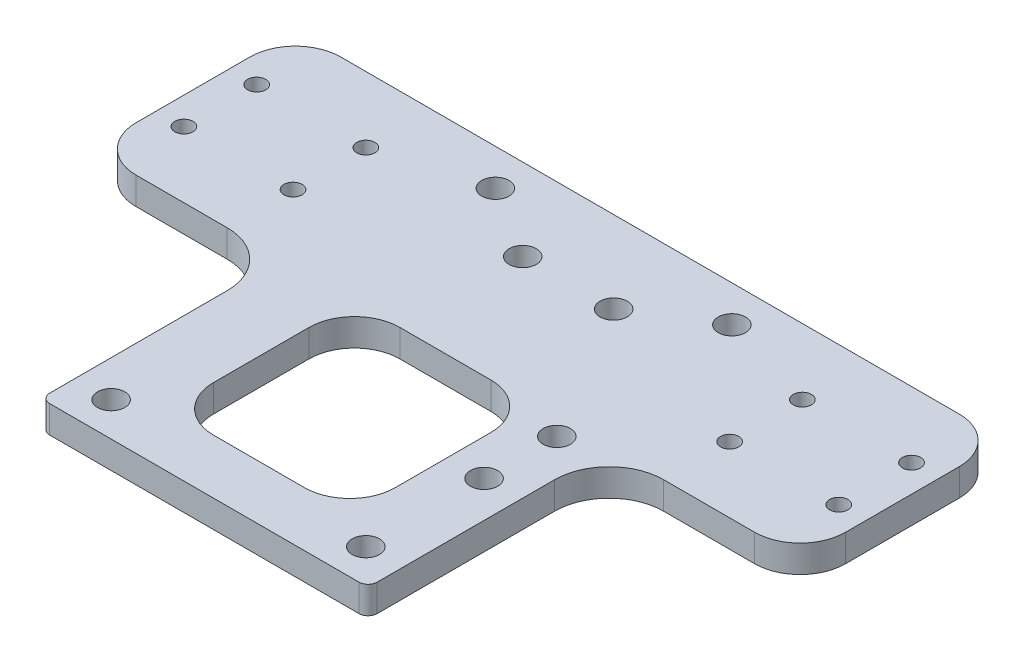
SolidWorks part; units mm, degrees
material "Thornel Mat VMA"
ref_plane "前视基准面" through (0, 0, 0) normal (0, 0, 1) x (1, 0, 0)
ref_plane "上视基准面" through (0, 0, 0) normal (0, 1, 0) x (1, 0, 0)
ref_plane "右视基准面" through (0, 0, 0) normal (1, 0, 0) x (0, 0, -1)
other "Configuration Table"
sketch "草图1" plane through (0, 0, 0) normal (0, 1, 0) x (1, 0, 0)
  line L0 (0, 0) -> (0, 37.5652) construction
  line L1 (-39, -11.25) -> (39, -11.25)
  line L2 (-39, -11.25) -> (-39, 11.25)
  line L3 (-39, 11.25) -> (39, 11.25)
  line L4 (39, -11.25) -> (39, 11.25)
  line L5 (-39, -11.25) -> (39, 11.25) construction
  line L6 (-39, 11.25) -> (39, -11.25) construction
  line L7 (0, 0) -> (52.1691, 0) construction
  line L8 (30, 0) -> (30, 35.0489) construction
  circle A0 centre (36, 4) radius 1
  circle A1 centre (24, 4) radius 1
  circle A2 centre (36, -4) radius 1
  circle A3 centre (24, -4) radius 1
  circle A4 centre (-24, -4) radius 1
  circle A5 centre (-36, -4) radius 1
  circle A6 centre (-24, 4) radius 1
  circle A7 centre (-36, 4) radius 1
  point P0 (0, 0)
  dimension "D3" = 2
  dimension "D4" = 12
  dimension "D5" = 8
  dimension "D1" = 78
  dimension "D2" = 22.5
  dimension "D6" = 30
extrude "凸台-拉伸1" add sketch "草图1" along normal blind 3
fillet "圆角1" radius 5 4 edges at (-39, 1.5, -11.25) (-39, 1.5, 11.25) (39, 1.5, -11.25) (39, 1.5, 11.25)
sketch "草图2" plane through (0, 3, 0) normal (0, 1, 0) x (1, 0, 0)
  line L0 (0, 0) -> (0, 76.4951) construction
  line L1 (0, 0) -> (49.7952, 0) construction
  line L2 (-10, -11.25) -> (-18, -11.25)
  line L12 (-10, -37.75) -> (10, -37.75)
  line L73 (-34, -11.25) -> (34, -11.25) construction
  line L74 (18, -11.25) -> (18, -37.75)
  line L79 (10, -37.75) -> (18, -37.75)
  line L80 (10, -37.75) -> (10, -11.25)
  line L81 (10, -11.25) -> (18, -11.25)
  line L82 (-10, -37.75) -> (-10, -11.25)
  line L83 (-10, -37.75) -> (-18, -37.75)
  line L84 (-18, -11.25) -> (-18, -37.75)
  line L85 (-10, -31.75) -> (10, -31.75)
  circle A0 centre (14, -8) radius 1.5
  circle A1 centre (14, -21) radius 1.5
  circle A2 centre (-14, -21) radius 1.5
  circle A3 centre (-14, -8) radius 1.5
  point P85 (0, -11.25)
  line M8 (-34, -11.25) -> (34, -11.25)
  dimension "D20" = 3
  dimension "D21" = 3
  dimension "D22" = 13
  dimension "D23" = 8
  dimension "D25" = 14
  dimension "D3" = 6
  dimension "D18" = 26.5
  dimension "D19" = 10
  dimension "D24" = 14
  dimension "D26" = 8
extrude "凸台-拉伸2" add sketch "草图2" against normal blind 3 contours L84 L83 L82 A2 M8 | A2 | L80 L79 L74 A1 M8 | L85 L82 L12 L80
sketch "草图4" plane through (0, 3, 0) normal (0, 1, 0) x (1, 0, 0)
  line L0 (0, 0) -> (0, 68.3495) construction
  line L2 (34, 11.25) -> (-34, 11.25) construction
  circle A2 centre (13, 7.25) radius 1.5
  circle A3 centre (-13, 7.25) radius 1.5
  circle A5 centre (5, 2.25) radius 1.5
  circle A6 centre (-5, 2.25) radius 1.5
  dimension "D1" = 3
  dimension "D2" = 10
  dimension "D4" = 3
  dimension "D5" = 13
  dimension "D6" = 4
  dimension "D3" = 5
extrude "切除-拉伸1" cut sketch "草图4" against normal blind 29.5
sketch "草图6" plane through (0, 3, 0) normal (0, 1, 0) x (1, 0, 0)
  line L0 (0, 0) -> (0, -39.0261) construction
  line L1 (0, 0) -> (42.2045, 0) construction
  circle A0 centre (14, -13) radius 1.5
  circle A2 centre (-14, -13) radius 1.5
  dimension "D1" = 3
  dimension "D3" = 13
  dimension "D2" = 14
extrude "切除-拉伸3" cut sketch "草图6" against normal blind 39 contours A0
fillet "圆角7" radius 6 2 edges at (18, 1.5, 11.25) (-18, 1.5, 11.25)
sketch "草图7" plane through (0, 3, 0) normal (0, 1, 0) x (1, 0, 0)
  line L0 (14, -13) -> (14, -45.5392) construction
  line L1 (0, 0) -> (0, -27.3122) construction
  circle A0 centre (14, -34) radius 1.5
  circle A1 centre (14, -21) radius 1.5 construction
  circle A2 centre (-14, -34) radius 1.5
  dimension "D1" = 3
  dimension "D2" = 13
extrude "切除-拉伸4" cut sketch "草图7" against normal blind 10
fillet "圆角9" radius 1 2 edges at (18, 1.5, 37.75) (-18, 1.5, 37.75)
fillet "圆角10" radius 5 4 edges at (-10, 1.5, 31.75) (10, 1.5, 31.75) (10, 1.5, 11.25) (-10, 1.5, 11.25)
